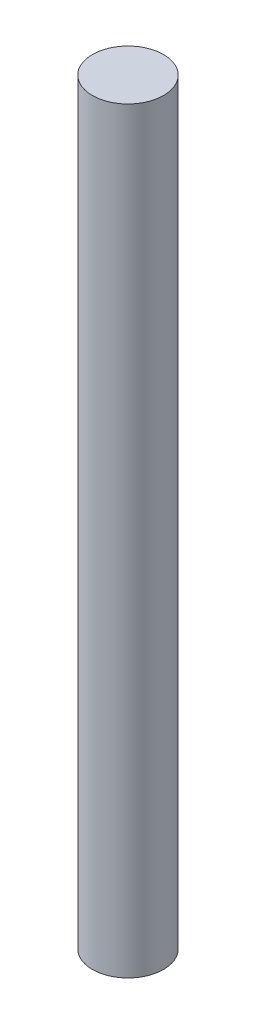
SolidWorks part; units mm, degrees
ref_plane "Front Plane" through (0, 0, 0) normal (0, 0, 1) x (1, 0, 0)
ref_plane "Top Plane" through (0, 0, 0) normal (0, 1, 0) x (1, 0, 0)
ref_plane "Right Plane" through (0, 0, 0) normal (1, 0, 0) x (0, 0, -1)
sketch "Sketch1" plane through (0, 0, 0) normal (0, 1, 0) x (1, 0, 0)
  circle A0 centre (0, 0) radius 10
extrude "Boss-Extrude1" add sketch "Sketch1" along normal blind 213
